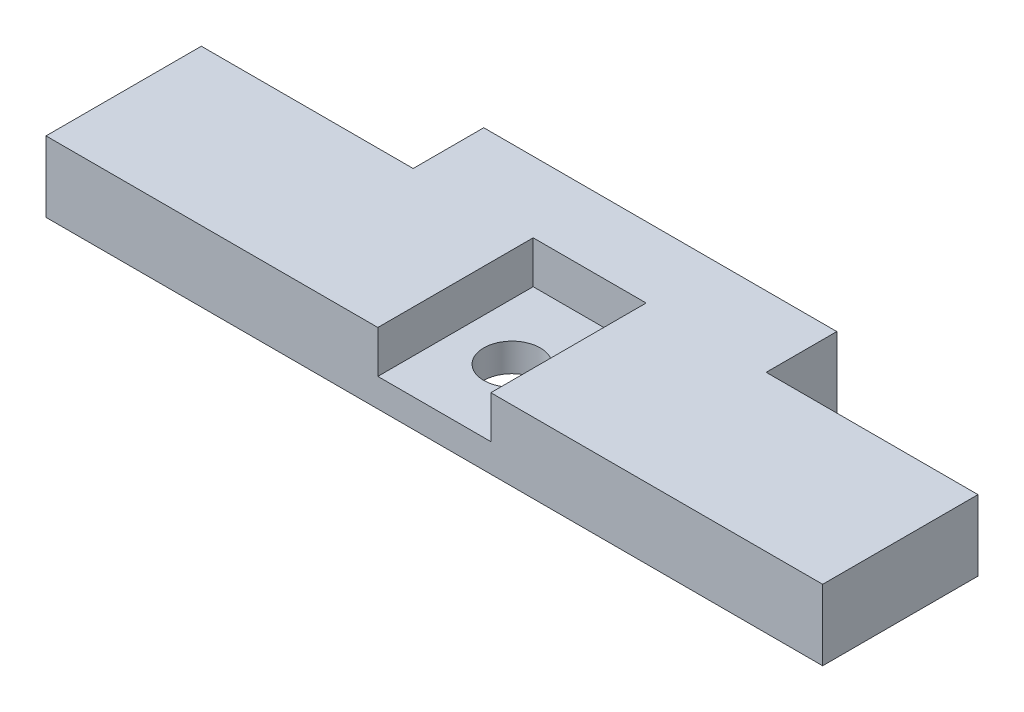
SolidWorks part; units mm, degrees
ref_plane "Plan de face" through (0, 0, 0) normal (0, 0, 1) x (1, 0, 0)
ref_plane "Plan de dessus" through (0, 0, 0) normal (0, 1, 0) x (1, 0, 0)
ref_plane "Plan de droite" through (0, 0, 0) normal (1, 0, 0) x (0, 0, -1)
sketch "Esquisse1" plane through (0, 0, 0) normal (0, 1, 0) x (1, 0, 0)
  line L0 (-12.5, 8) -> (-12.5, 3)
  line L1 (-12.5, 8) -> (12.5, 8)
  line L2 (-27.5, 3) -> (-27.5, -8)
  line L3 (-27.5, -8) -> (27.5, -8)
  line L4 (27.5, 3) -> (27.5, -8)
  line L5 (-27.5, 8) -> (27.5, -8) construction
  line L6 (-27.5, -8) -> (27.5, 8) construction
  line L7 (12.5, 8) -> (12.5, 3)
  line L8 (-12.5, 3) -> (-27.5, 3)
  line L9 (12.5, 3) -> (27.5, 3)
  point P0 (0, 0)
  dimension "D1" = 55
  dimension "D2" = 15
  dimension "D3" = 15
  dimension "D4" = 5
  dimension "D5" = 16
extrude "Boss.-Extru.1" add sketch "Esquisse1" along normal blind 5
sketch "Esquisse2" plane through (0, 5, 0) normal (0, 1, 0) x (1, 0, 0)
  line L0 (4, -8) -> (4, 3)
  line L1 (-27.5, -8) -> (27.5, -8) construction
  line L2 (0, 11.8242) -> (0, -16.0323) construction
  line L3 (-4, -8) -> (-4, 3)
  line L4 (4, 3) -> (-4, 3)
  line L5 (4, -8) -> (-4, -8)
  dimension "D1" = 11
  dimension "D2" = 8
extrude "Enlèv. mat.-Extru.5" cut sketch "Esquisse2" against normal blind 3
sketch "Esquisse3" plane through (0, 2, 0) normal (0, 1, 0) x (1, 0, 0)
  line L0 (-4, -8) -> (4, -8) construction
  circle A0 centre (0, -2.5) radius 2
  dimension "D1" = 4
  dimension "D2" = 5.5
extrude "Enlèv. mat.-Extru.6" cut sketch "Esquisse3" against normal through all
